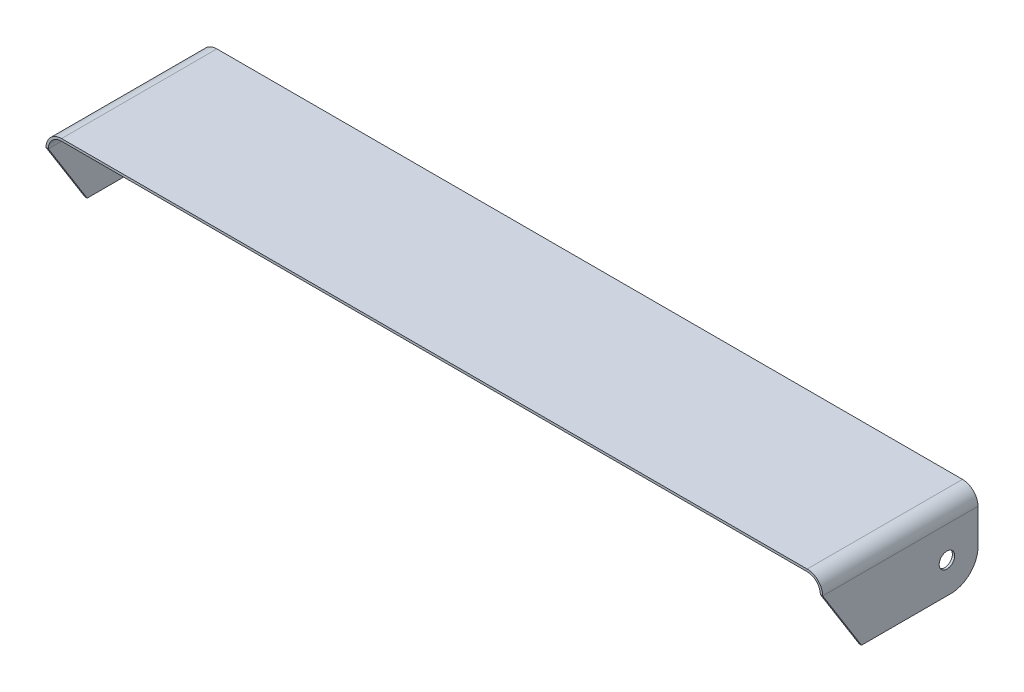
SolidWorks part; units mm, degrees
ref_plane "Front Plane" through (0, 0, 0) normal (0, 0, 1) x (1, 0, 0)
ref_plane "Top Plane" through (0, 0, 0) normal (0, 1, 0) x (1, 0, 0)
ref_plane "Right Plane" through (0, 0, 0) normal (1, 0, 0) x (0, 0, -1)
sketch "Sketch1" plane through (0, 0, 0) normal (0, 0, 1) x (1, 0, 0)
  line L0 (-500, 0) -> (-500, 80)
  line L1 (-480, 100) -> (480, 100)
  line L2 (500, 80) -> (500, 0)
  line L3 (-497, 0) -> (-497, 80)
  line L4 (-480, 97) -> (480, 97)
  line L5 (497, 80) -> (497, 0)
  line L6 (497, 0) -> (500, 0)
  line L7 (-500, 0) -> (-497, 0)
  arc A0 (480, 100) -> (500, 80) centre (480, 80) cw
  arc A1 (-500, 80) -> (-480, 100) centre (-480, 80) cw
  arc A2 (-497, 80) -> (-480, 97) centre (-480, 80) cw
  arc A3 (480, 97) -> (497, 80) centre (480, 80) cw
  point P8 (500, 100)
  point P11 (-500, 100)
  dimension "D4" = 20
  dimension "D1" = 1000
  dimension "D2" = 500
  dimension "D3" = 100
  dimension "D5" = 3
extrude "Boss-Extrude1" add sketch "Sketch1" along normal mid plane 200
sketch "Sketch2" plane through (500, 0, 0) normal (1, 0, 0) x (0, 0, -1)
  line L0 (-100, 80) -> (-100, 0)
  line L1 (-100, 0) -> (-50, 0)
  line L2 (-100, 0) -> (100, 0) construction
  line L3 (-50, 0) -> (-100, 80)
  dimension "D1" = 50
  dimension "D2" = 80
extrude "Cut-Extrude1" cut sketch "Sketch2" against normal through all
sketch "Sketch3" plane through (500, 0, 0) normal (1, 0, 0) x (0, 0, -1)
  line L0 (-100, 100) -> (100, 100) construction
  circle A0 centre (60, 40) radius 10
  dimension "D3" = 20
  dimension "D1" = 60
  dimension "D2" = 40
extrude "Cut-Extrude2" cut sketch "Sketch3" against normal through all
fillet "Fillet1" radius 35 2 edges at (-498.5, 0, -100) (498.5, 0, -100)
